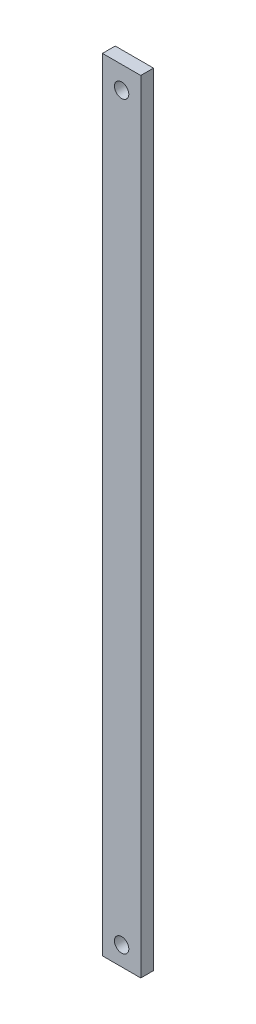
SolidWorks part; units mm, degrees
ref_plane "Front Plane" through (0, 0, 0) normal (0, 0, 1) x (1, 0, 0)
ref_plane "Top Plane" through (0, 0, 0) normal (0, 1, 0) x (1, 0, 0)
ref_plane "Right Plane" through (0, 0, 0) normal (1, 0, 0) x (0, 0, -1)
sketch "Sketch1" plane through (0, 0, 0) normal (0, 0, 1) x (1, 0, 0)
  line L1 (0, 0) -> (12, 0)
  line L2 (0, 0) -> (0, 245)
  line L3 (0, 245) -> (12, 245)
  line L4 (12, 0) -> (12, 245)
  dimension "D1" = 12
  dimension "D2" = 245
extrude "Profile" add sketch "Sketch1" along normal blind 4
sketch "Sketch2" plane through (0, 0, 0) normal (0, 0, 1) x (1, 0, 0)
  circle A0 centre (6, 6) radius 2.25
  circle A1 centre (6, 238) radius 2.25
  dimension "D1" = 4.5
  dimension "D2" = 4.5
  dimension "D3" = 232
extrude "Fastener_clearance" cut sketch "Sketch2" against normal through all and the other way through all
equation "\"Profile_Depth\"= 4mm"
equation "\"D1@Profile\" = \"Profile_Depth\""
equation "\"Profile_Sketch_1\"= 12mm"
equation "\"D1@Sketch1\" = \"Profile_Sketch_1\""
equation "\"Profile_Sketch_2\"= 245mm"
equation "\"D2@Sketch1\" = \"Profile_Sketch_2\""
equation "\"EnvelopeWidth\"= 12mm"
equation "\"EnvelopeHeight\"= 245mm"
